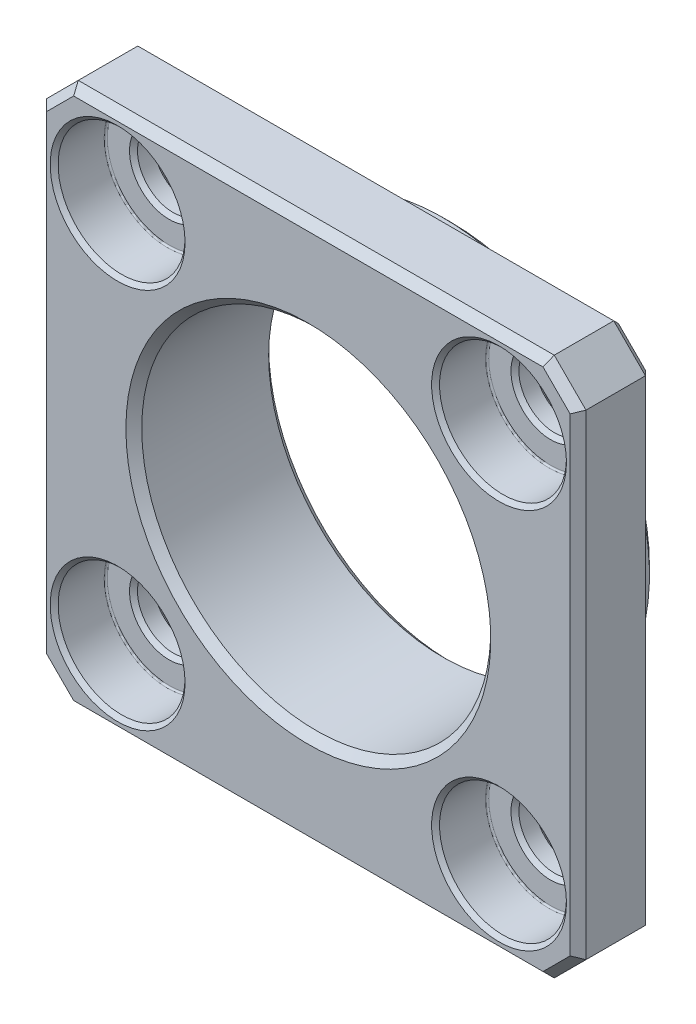
SolidWorks part; units mm, degrees
material "1023 Carbon Steel Sheet (SS)"
ref_plane "Front Plane" through (0, 0, 0) normal (0, 0, 1) x (1, 0, 0)
ref_plane "Top Plane" through (0, 0, 0) normal (0, 1, 0) x (1, 0, 0)
ref_plane "Right Plane" through (0, 0, 0) normal (1, 0, 0) x (0, 0, -1)
sketch "BK Flange Sketch" plane through (0, 0, 0) normal (0, 0, 1) x (1, 0, 0)
  line L1 (-17, -17) -> (17, -17)
  line L2 (-17, -17) -> (-17, 17)
  line L3 (-17, 17) -> (17, 17)
  line L4 (17, -17) -> (17, 17)
  line L5 (-17, -17) -> (17, 17) construction
  line L6 (-17, 17) -> (17, -17) construction
  point P0 (0, 0)
  dimension "B1" = 34
extrude "BK Flange Body" add sketch "BK Flange Sketch" along normal blind 4.75
sketch "BK Flange Radius Sketch" plane through (0, 0, 0) normal (0, 0, -1) x (-1, 0, 0)
  circle A0 centre (0, 0) radius 13
  dimension "DO" = 26
extrude "BK Flange Radius" add sketch "BK Flange Radius Sketch" along normal blind 4.25
sketch "BK Flange H" plane through (0, 0, -4.25) normal (0, 0, -1) x (-1, 0, 0)
  circle A0 centre (0, 0) radius 11
  dimension "DOS" = 22
extrude "BK Flange Hole" cut sketch "BK Flange H" against normal through all both and the other way through all
hole_wizard "BK Flange Holes" positions "Sketch1" profile "Sketch2" counterbore size "M4" standard "ISO" end condition through all
sketch "Sketch1" plane through (0, 0, 4.75) normal (0, 0, 1) x (1, 0, 0)
  line L0 (12.0208, 12.0208) -> (-12.0208, -12.0208) construction
  line L6 (-12.0208, -12.0208) -> (-12.0208, 12.0208) construction
  line L8 (-12.0208, 12.0208) -> (12.0208, 12.0208) construction
  point P0 (-12.0208, 12.0208)
  point P2 (12.0208, 12.0208)
  point P4 (12.0208, -12.0208)
  point P6 (-12.0208, -12.0208)
  point P17 (0, 0)
  dimension "rf" = 34
sketch "Sketch2" plane through (-12.0208, 12.0208, 4.75) normal (1, 0, 0) x (0, -1, 0)
  line L0 (0, 0) -> (0, 4.75)
  line L1 (2.25, 4.5) -> (2.5, 4.75)
  line L2 (2.25, 4.5) -> (2.25, 3.5)
  line L3 (2.25, 3.5) -> (2.5, 3.25)
  line L4 (2.5, 3.25) -> (4, 3.25)
  line L5 (4, 3.25) -> (4, 0.25)
  line L6 (4, 0.25) -> (4.25, 0)
  line L7 (4.25, 0) -> (0, 0)
  line L8 (-4, 0.25) -> (-4.25, 0) construction
  line L9 (-2.25, 3.5) -> (-2.5, 3.25) construction
  line L11 (0, -6.35) -> (0, 107.95) construction
  line L12 (2.5, 4.75) -> (0, 4.75)
  line L13 (-2.25, 4.5) -> (-2.5, 4.75) construction
  dimension "Thru Hole Dia." = 4.5
  dimension "Thru Hole Depth" = 4.75
  dimension "C'Bore Dia." = 8
  dimension "C'Bore Depth" = 3.25
  dimension "Near C'Sink Dia." = 8.5
  dimension "Near C'Sink Angle" = 90
  dimension "Mid C'Sink Dia." = 5
  dimension "Mid C'Sink Angle" = 90
  dimension "Far C'Sink Dia." = 5
  dimension "Far C'Sink Angle" = 90
chamfer "BK Corner Chamfer" distance 2 angle 45 4 edges at (-17, -17, 2.375) (17, -17, 2.375) (17, 17, 2.375) (-17, 17, 2.375)
fillet "Production Fillet" radius 0.1 5 edges at (-13, 0, 0) (16.0208, -12.0208, 1.5) (16.0208, 12.0208, 1.5) (-8.0208, 12.0208, 1.5) (-8.0208, -12.0208, 1.5)
chamfer "Aesthetic Chamfer" distance 0.5 angle 45 19 edges at (-11, 0, 4.75) (-11, 0, -4.25) (-13, 0, -4.25) (-16, 16, 0) (-17, 0, 0) (-16, -16, 0) (0, -17, 0) (16, -16, 0) (17, 0, 0) (0, 17, 0) (16, 16, 0) (16, 16, 4.75) (17, 0, 4.75) (16, -16, 4.75) (0, -17, 4.75) (-16, -16, 4.75) (-17, 0, 4.75) (-16, 16, 4.75) (0, 17, 4.75)
equation "\"Near C'Sink Dia.@Sketch2\"= \"C'Bore Dia.@Sketch2\" + 0.5"
equation "\"Mid C'Sink Dia.@Sketch2\"= \"Thru Hole Dia.@Sketch2\" + 0.5"
equation "\"Far C'Sink Dia.@Sketch2\"= \"Thru Hole Dia.@Sketch2\" + 0.5"
